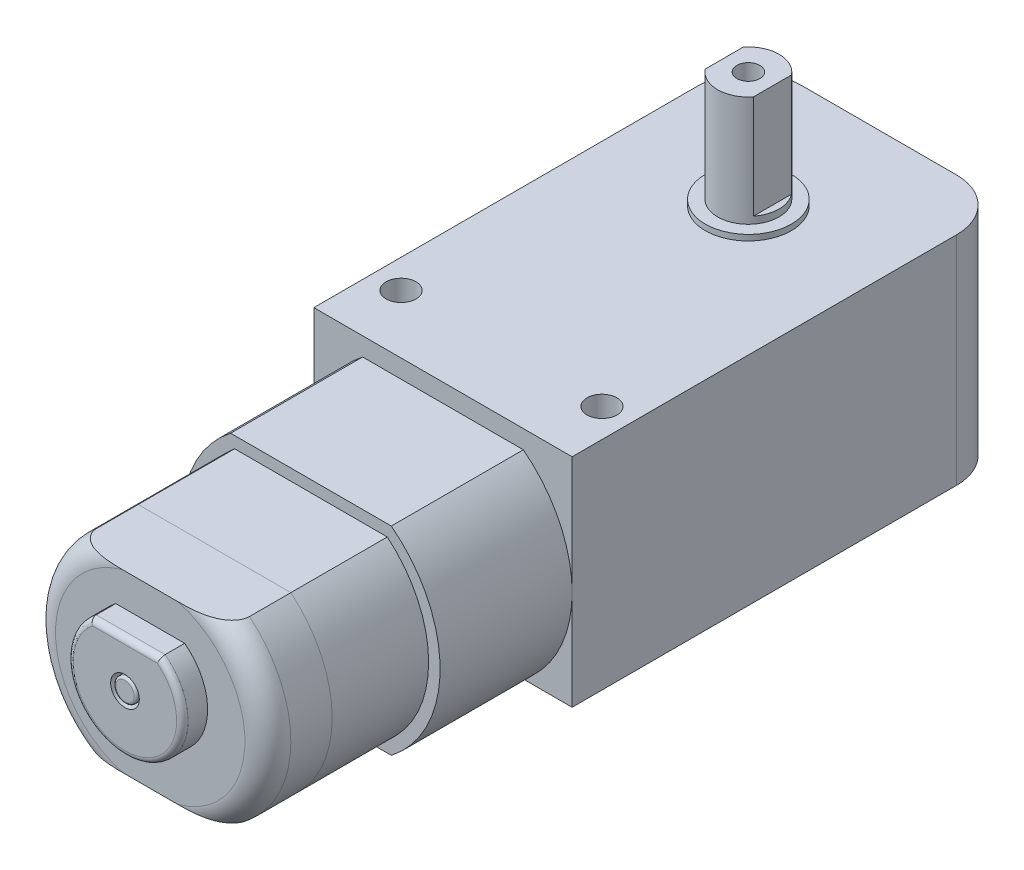
SolidWorks part; units mm, degrees
ref_plane "Front Plane" through (0, 0, 0) normal (0, 0, 1) x (1, 0, 0)
ref_plane "Top Plane" through (0, 0, 0) normal (0, 1, 0) x (1, 0, 0)
ref_plane "Right Plane" through (0, 0, 0) normal (1, 0, 0) x (0, 0, -1)
sketch "Sketch1" plane through (0, 0, 0) normal (0, 1, 0) x (1, 0, 0)
  line L1 (11.25, 19) -> (-11.25, 19)
  line L2 (11.25, 19) -> (11.25, -19)
  line L3 (11.25, -19) -> (-11.25, -19)
  line L4 (-11.25, 19) -> (-11.25, -19)
  line L5 (11.25, 19) -> (-11.25, -19) construction
  line L6 (11.25, -19) -> (-11.25, 19) construction
  point P0 (0, 0)
  dimension "D1" = 22.5
  dimension "D2" = 38
extrude "Boss-Extrude1" add sketch "Sketch1" along normal mid plane 18.9
fillet "Fillet1" radius 4.5 2 edges at (-11.25, 0, -19) (11.25, 0, -19)
sketch "Sketch2" plane through (0, 0, 19) normal (0, 0, 1) x (1, 0, 0)
  line L0 (-11.25, -9.45) -> (11.25, -9.45) construction
  line L5 (7, -9.45) -> (-7, -9.45)
  line L7 (7, 7.85) -> (-7, 7.85)
  line L9 (7, -9.45) -> (-7, 7.85) construction
  line L10 (7, 7.85) -> (-7, -9.45) construction
  line L13 (-11.25, 9.45) -> (-11.25, -9.45) construction
  arc A0 (-7, 7.85) -> (-7, -9.45) centre (-0.3224, -0.8) ccw
  arc A1 (7, 7.85) -> (7, -9.45) centre (0.3224, -0.8) cw
  point P0 (0, -0.8)
  dimension "D3" = 10.9276
  dimension "D1" = 17.3
  dimension "D2" = 14
extrude "Boss-Extrude2" add sketch "Sketch2" along normal blind 11.5
sketch "Sketch3" plane through (0, 0, 30.5) normal (0, 0, 1) x (1, 0, 0)
  line L4 (-6.6497, -8.45) -> (6.6497, -8.45)
  line L5 (6.6497, 6.85) -> (-6.6497, 6.85)
  line L6 (-6.6497, -8.45) -> (6.6497, -8.45)
  line L7 (6.6497, 6.85) -> (-6.6497, 6.85)
  arc A4 (-6.6497, 6.85) -> (-6.6497, -8.45) centre (-0.3224, -0.8) ccw
  arc A5 (6.6497, -8.45) -> (6.6497, 6.85) centre (0.3224, -0.8) ccw
  arc A6 (-6.6497, 6.85) -> (-6.6497, -8.45) centre (-0.3224, -0.8) ccw
  arc A7 (6.6497, -8.45) -> (6.6497, 6.85) centre (0.3224, -0.8) ccw
  dimension "D1" = 1
extrude "Cut-Extrude1" cut sketch "Sketch3" against normal up to surface (11.5 mm away) up to face at (0, 5.6646, 19)
sketch "Sketch4" plane through (0, 0, 0) normal (0, 1, 0) x (1, 0, 0)
  line L0 (6.75, 19) -> (-6.75, 19) construction
  line L1 (2.5, 19) -> (-2.5, 19)
  line L2 (2.5, 19) -> (2.5, 24)
  line L3 (2.5, 24) -> (-2.5, 24)
  line L4 (-2.5, 19) -> (-2.5, 24)
  line L5 (2.5, 19) -> (-2.5, 24) construction
  line L6 (2.5, 24) -> (-2.5, 19) construction
  circle A0 centre (0, 21.5) radius 1.25
  point P0 (0, 21.5)
  dimension "D3" = 2.5
  dimension "D1" = 5
  dimension "D2" = 5
extrude "Boss-Extrude3" add sketch "Sketch4" along normal mid plane 2.5 contours L4 L1 L2 L3 A0
sketch "Sketch5" plane through (0, 9.45, 0) normal (0, 1, 0) x (1, 0, 0)
  line L0 (0, 24) -> (0, 0) construction
  line L1 (2.5, 24) -> (-2.5, 24) construction
  line L2 (6.75, 19) -> (-6.75, 19) construction
  circle A0 centre (0, 7.6) radius 3.75
  dimension "D1" = 7.5
  dimension "D2" = 11.4
extrude "Boss-Extrude4" add sketch "Sketch5" along normal blind 0.5
sketch "Sketch6" plane through (0, 9.95, 0) normal (0, 1, 0) x (1, 0, 0)
  circle A0 centre (0, 7.6) radius 2.675
  dimension "D1" = 5.35
extrude "Boss-Extrude5" add sketch "Sketch6" along normal blind 9.6 and the other way blind 27.4
sketch "Sketch7" plane through (0, 19.55, 0) normal (0, 1, 0) x (1, 0, 0)
  line L0 (-2.1, 9.257) -> (-2.1, 5.943)
  line L1 (2.1, 9.257) -> (2.1, 5.943)
  line L2 (-2.1, 7.6) -> (2.1, 7.6) construction
  circle A0 centre (0, 7.6) radius 2.675 construction
  circle A1 centre (0, 7.6) radius 2.675 construction
  arc A2 (2.1, 5.943) -> (2.1, 9.257) centre (0, 7.6) ccw
  circle A3 centre (0, 7.6) radius 2.675
  arc A4 (-2.1, 9.257) -> (-2.1, 5.943) centre (0, 7.6) ccw
  point P10 (0, 7.6)
  dimension "D2" = 4.2
  dimension "D1" = 0
extrude "Cut-Extrude4" cut sketch "Sketch7" against normal blind 9
sketch "Sketch8" plane through (0, 19.55, 0) normal (0, 1, 0) x (1, 0, 0)
  circle A0 centre (0, 7.6) radius 1
  dimension "D1" = 2
extrude "Cut-Extrude5" cut sketch "Sketch8" against normal up to surface (9 mm away) up to face at (-2.3875, 10.55, -7.6)
fillet "Fillet2" radius 0.5 2 edges at (2.5, 0, -24) (-2.5, 0, -24)
sketch "Sketch9" plane through (0, 0, 19) normal (0, 0, 1) x (1, 0, 0)
  line L2 (-6.6497, -8.45) -> (6.6497, -8.45)
  line L3 (6.6497, 6.85) -> (-6.6497, 6.85)
  line L4 (-6.6497, -8.45) -> (6.6497, -8.45)
  line L5 (6.6497, 6.85) -> (-6.6497, 6.85)
  arc A2 (-6.6497, 6.85) -> (-6.6497, -8.45) centre (-0.3224, -0.8) ccw
  arc A3 (6.6497, -8.45) -> (6.6497, 6.85) centre (0.3224, -0.8) ccw
  arc A4 (-6.6497, 6.85) -> (-6.6497, -8.45) centre (-0.3224, -0.8) ccw
  arc A5 (6.6497, -8.45) -> (6.6497, 6.85) centre (0.3224, -0.8) ccw
  dimension "D1" = 0
extrude "Boss-Extrude6" add sketch "Sketch9" along normal blind 27.7 separate body
sketch "Sketch10" plane through (0, 6.85, 0) normal (0, 1, 0) x (1, 0, 0)
  line L0 (-10.25, -38.9) -> (10.25, -38.9)
  line L1 (-10.25, -19) -> (-10.25, -46.7) construction
  line L2 (10.25, -46.7) -> (10.25, -19) construction
  line L3 (7, -30.5) -> (-7, -30.5) construction
  dimension "D1" = 8.4
split "Split1" trim tools "Sketch10" bodies to split 109 resulting bodies 110 111
sketch "Sketch11" plane through (0, 0, 46.7) normal (0, 0, 1) x (1, 0, 0)
  line L0 (-3, 4) -> (3, 4)
  line L3 (-6.6497, -8.45) -> (6.6497, -8.45)
  line L4 (6.6497, 6.85) -> (-6.6497, 6.85)
  line L5 (-6.6497, -8.45) -> (6.6497, -8.45)
  line L6 (6.6497, 6.85) -> (-6.6497, 6.85)
  arc A0 (-3, 4) -> (3, 4) centre (0, 0) ccw
  arc A3 (-6.6497, 6.85) -> (-6.6497, -8.45) centre (-0.3224, -0.8) ccw
  arc A7 (-6.6497, 6.85) -> (-6.6497, -8.45) centre (-0.3224, -0.8) ccw
  arc A9 (6.6497, -8.45) -> (6.6497, 6.85) centre (0.3224, -0.8) ccw
  arc A10 (6.6497, -8.45) -> (6.6497, 6.85) centre (0.3224, -0.8) ccw
  dimension "D1" = 10
  dimension "D2" = 9
  dimension "D3" = 0
extrude "Cut-Extrude6" cut sketch "Sketch11" against normal blind 2.2
fillet "Fillet4" radius 0.5 2 edges at (0, -5, 46.7) (0, 4, 46.7)
fillet "Fillet3" radius 2 2 edges at (-10.25, -0.8, 44.5) (10.25, -0.8, 44.5)
sketch "Sketch12" plane through (0, 0, 46.7) normal (0, 0, 1) x (1, 0, 0)
  circle A0 centre (0, 0) radius 1.25
  dimension "D1" = 2.5
extrude "Cut-Extrude7" cut sketch "Sketch12" against normal up to surface (2.2 mm away) up to face at (0, -0.5, 44.5)
sketch "Sketch13" plane through (0, 0, 44.5) normal (0, 0, 1) x (1, 0, 0)
  circle A0 centre (0, 0) radius 1
  dimension "D1" = 2
extrude "Boss-Extrude7" add sketch "Sketch13" along normal up to surface (2.2 mm away) up to face at (1.25, 0, 46.7)
fillet "Fillet5" radius 0.2 1 edges at (1, 0, 46.7)
sketch "Sketch14" plane through (0, 9.45, 0) normal (0, 1, 0) x (1, 0, 0)
  line L0 (-8.75, -13.9) -> (8.75, -13.9) construction
  line L1 (11.25, -19) -> (11.25, 14.5) construction
  line L4 (7, -19) -> (11.25, -19) construction
  circle A0 centre (-8.75, -13.9) radius 1.3
  circle A1 centre (8.75, -13.9) radius 1.3
  point P11 (0, -13.9)
  dimension "D1" = 2.6
  dimension "D2" = 2.5
  dimension "D3" = 5.1
extrude "Cut-Extrude8" cut sketch "Sketch14" against normal up to surface (18.9 mm away) up to face at (0, -9.45, -10.275)
equation "\"D2@Sketch14\"= 1.2 + (\"D1@Sketch14\"/2)"
equation "\"D3@Sketch14\"=3.8 + (\"D1@Sketch14\"/2)"
